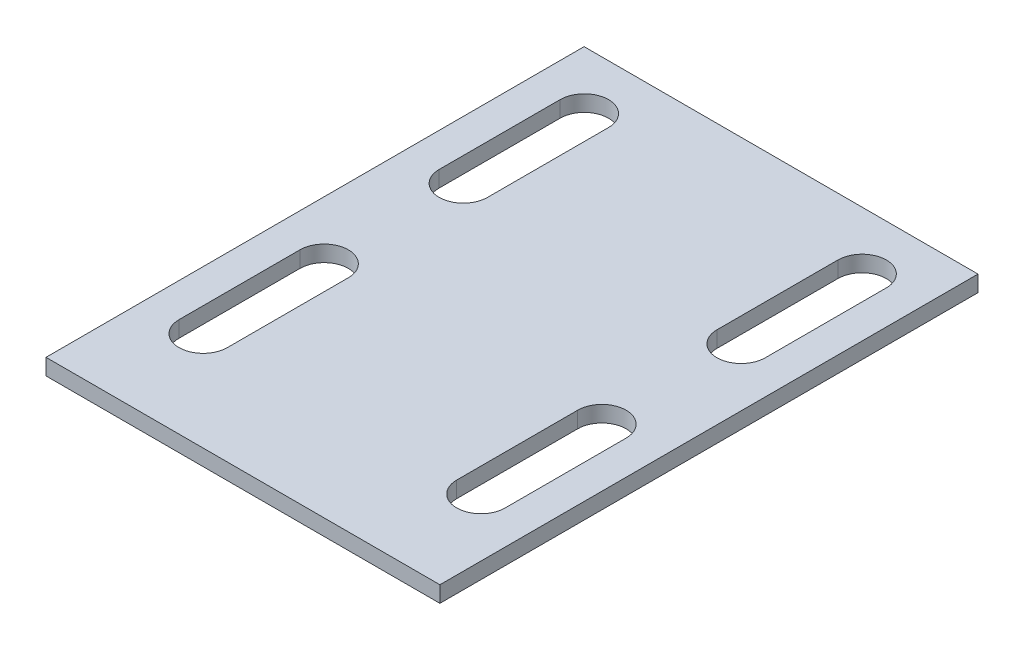
SolidWorks part; units mm, degrees
ref_plane "Front" through (0, 0, 0) normal (0, 0, 1) x (1, 0, 0)
ref_plane "Top" through (0, 0, 0) normal (0, 1, 0) x (1, 0, 0)
ref_plane "Right" through (0, 0, 0) normal (1, 0, 0) x (0, 0, -1)
sketch "Sketch1" plane through (0, 0, 0) normal (0, 1, 0) x (1, 0, 0)
  line L1 (0, 0) -> (122.1, 0)
  line L2 (0, 0) -> (0, 197.8)
  line L3 (0, 197.8) -> (122.1, 197.8)
  line L4 (122.1, 0) -> (122.1, 197.8)
  dimension "D1" = 122.1
  dimension "D2" = 197.8
extrude "Boss-Extrude2" add sketch "Sketch1" along normal blind 5 contours L2 L3 L4 L1
sketch "Sketch3" plane through (0, 5, 0) normal (0, 1, 0) x (1, 0, 0)
  line L0 (18, 167.875) -> (18, 130.375) construction
  line L1 (25.5, 167.875) -> (25.5, 130.375)
  line L2 (10.5, 167.875) -> (10.5, 130.375)
  line L3 (18, 87.2216) -> (18, 49.7216) construction
  line L4 (25.5, 87.2216) -> (25.5, 49.7216)
  line L5 (10.5, 87.2216) -> (10.5, 49.7216)
  line L7 (122.1, 0) -> (122.1, 197.8) construction
  line L8 (61.05, 197.8) -> (61.05, 0)
  line L9 (0, 197.8) -> (122.1, 197.8) construction
  line L10 (0, 0) -> (122.1, 0) construction
  line L11 (104.1, 87.2216) -> (104.1, 49.7216) construction
  line L12 (96.6, 87.2216) -> (96.6, 49.7216)
  line L13 (111.6, 87.2216) -> (111.6, 49.7216)
  line L14 (104.1, 167.875) -> (104.1, 130.375) construction
  line L15 (96.6, 167.875) -> (96.6, 130.375)
  line L16 (111.6, 167.875) -> (111.6, 130.375)
  arc A0 (25.5, 167.875) -> (10.5, 167.875) centre (18, 167.875) ccw
  arc A1 (10.5, 130.375) -> (25.5, 130.375) centre (18, 130.375) ccw
  arc A2 (25.5, 87.2216) -> (10.5, 87.2216) centre (18, 87.2216) ccw
  arc A3 (10.5, 49.7216) -> (25.5, 49.7216) centre (18, 49.7216) ccw
  arc A4 (96.6, 87.2216) -> (111.6, 87.2216) centre (104.1, 87.2216) cw
  arc A5 (111.6, 49.7216) -> (96.6, 49.7216) centre (104.1, 49.7216) cw
  arc A6 (96.6, 167.875) -> (111.6, 167.875) centre (104.1, 167.875) cw
  arc A7 (111.6, 130.375) -> (96.6, 130.375) centre (104.1, 130.375) cw
  point P2 (18, 149.125)
  point P9 (18, 68.4716)
  point P14 (18, 175.375)
  point P16 (18, 94.7216)
  point P27 (104.1, 68.4716)
  point P34 (104.1, 149.125)
  dimension "D1" = 45
  dimension "D2" = 15
  dimension "D3" = 15
  dimension "D4" = 45
  dimension "D5" = 96.6
extrude "Cut-Extrude1" cut sketch "Sketch3" against normal blind 5 contours L2 A1 L1 A0 | A7 L16 A6 L15 | A5 L13 A4 L12 | L5 A3 L4 A2
sketch "Sketch5" plane through (0, 0, -197.8) normal (0, 0, -1) x (-1, 0, 0)
  line L1 (41.638, -41.5201) -> (-135.0546, -41.5201)
  line L2 (41.638, -41.5201) -> (41.638, 26.3146)
  line L3 (41.638, 26.3146) -> (-135.0546, 26.3146)
  line L4 (-135.0546, -41.5201) -> (-135.0546, 26.3146)
extrude "Cut-Extrude2" cut sketch "Sketch5" against normal blind 12
sketch "Sketch6" plane through (0, 0, 0) normal (0, 0, 1) x (1, 0, 0)
  line L1 (-6.1951, 32.8599) -> (142.3082, 32.8599)
  line L2 (-6.1951, 32.8599) -> (-6.1951, -30.9989)
  line L3 (-6.1951, -30.9989) -> (142.3082, -30.9989)
  line L4 (142.3082, 32.8599) -> (142.3082, -30.9989)
extrude "Cut-Extrude3" cut sketch "Sketch6" against normal blind 19
